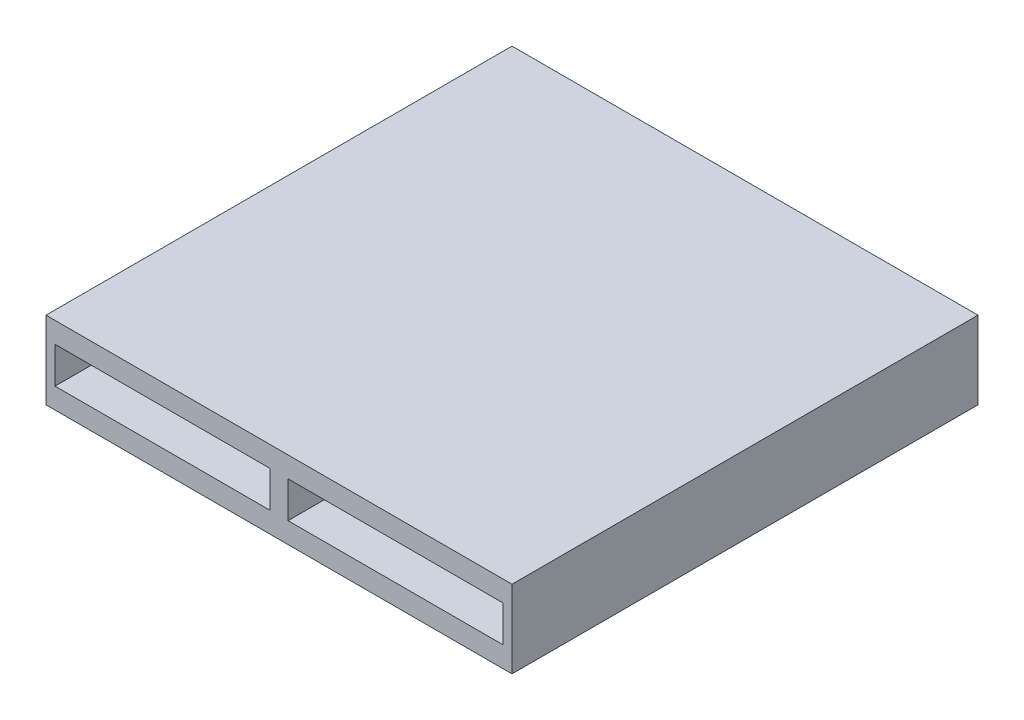
SolidWorks part; units mm, degrees
ref_plane "Front Plane" through (0, 0, 0) normal (0, 0, 1) x (1, 0, 0)
ref_plane "Top Plane" through (0, 0, 0) normal (0, 1, 0) x (1, 0, 0)
ref_plane "Right Plane" through (0, 0, 0) normal (1, 0, 0) x (0, 0, -1)
sketch "Sketch1" plane through (0, 0, 0) normal (0, 1, 0) x (1, 0, 0)
  line L1 (-45, 45) -> (45, 45)
  line L2 (-45, 45) -> (-45, -45)
  line L3 (-45, -45) -> (45, -45)
  line L4 (45, 45) -> (45, -45)
  line L5 (-45, 45) -> (45, -45) construction
  line L6 (-45, -45) -> (45, 45) construction
  point P0 (0, 0)
  dimension "D1" = 90
  dimension "D2" = 90
extrude "Boss-Extrude1" add sketch "Sketch1" along normal blind 15
sketch "Sketch2" plane through (0, 0, 45) normal (0, 0, 1) x (1, 0, 0)
  line L0 (0, 0) -> (0, 15) construction
  line L1 (-45, 15) -> (45, 15) construction
  line L2 (-45, 11) -> (45, 11) construction
  line L3 (-45, 15) -> (-45, 0) construction
  line L4 (45, 15) -> (45, 0) construction
  line L5 (-45, 4) -> (45, 4) construction
  line L6 (-45, 0) -> (45, 0) construction
  line L7 (-43.25, 15) -> (-43.25, 0) construction
  line L8 (-1.75, 15) -> (-1.75, 0) construction
  line L9 (1.75, 15) -> (1.75, 0) construction
  line L10 (43.25, 15) -> (43.25, 0) construction
  line L12 (-43.25, 11) -> (-1.75, 11)
  line L13 (-43.25, 11) -> (-43.25, 4)
  line L14 (-43.25, 4) -> (-1.75, 4)
  line L15 (-1.75, 11) -> (-1.75, 4)
  line L16 (1.75, 11) -> (43.25, 11)
  line L17 (1.75, 11) -> (1.75, 4)
  line L18 (1.75, 4) -> (43.25, 4)
  line L19 (43.25, 11) -> (43.25, 4)
  dimension "D1" = 4
  dimension "D2" = 4
  dimension "D3" = 1.75
  dimension "D4" = 1.75
  dimension "D5" = 1.75
  dimension "D6" = 1.75
extrude "Cut-Extrude1" cut sketch "Sketch2" against normal blind 90
